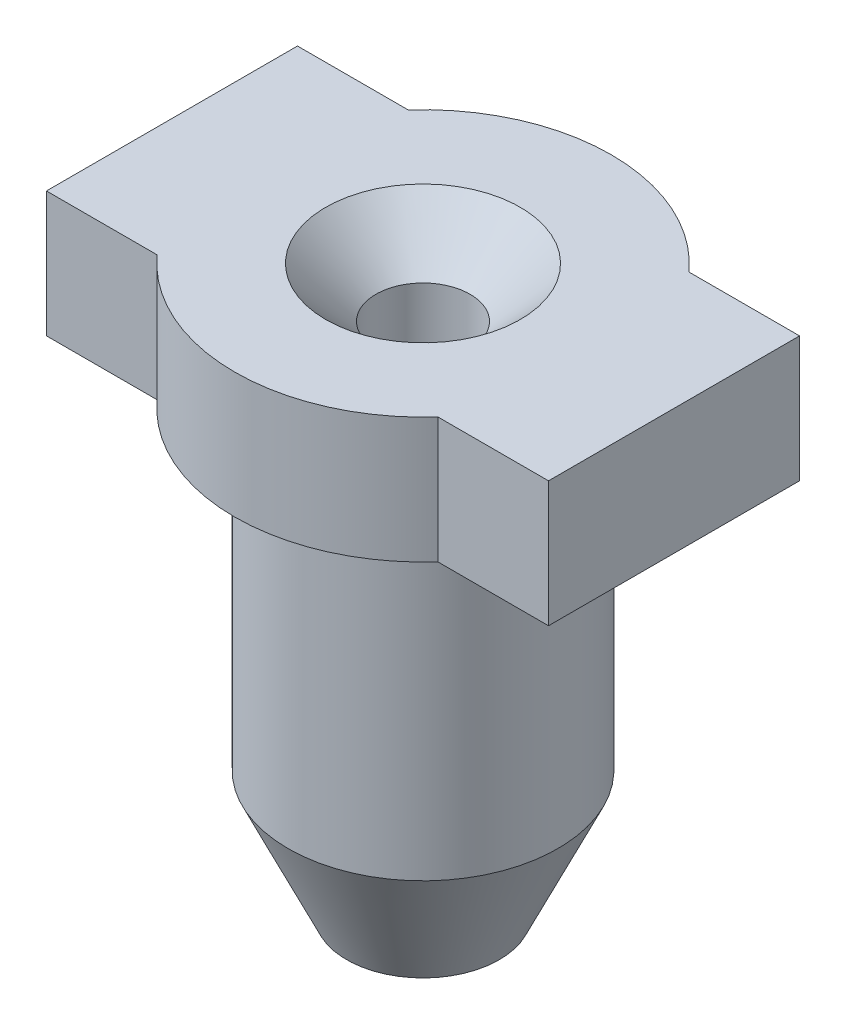
SolidWorks part; units mm, degrees
ref_plane "Front Plane" through (0, 0, 0) normal (0, 0, 1) x (1, 0, 0)
ref_plane "Top Plane" through (0, 0, 0) normal (0, 1, 0) x (1, 0, 0)
ref_plane "Right Plane" through (0, 0, 0) normal (1, 0, 0) x (0, 0, -1)
sketch "Sketch1" plane through (0, 0, 0) normal (0, 1, 0) x (1, 0, 0)
  circle A0 centre (0, 0) radius 15
  dimension "D1" = 30
extrude "Boss-Extrude1" add sketch "Sketch1" along normal blind 10
sketch "Sketch2" plane through (0, 0, 0) normal (0, -1, 0) x (1, 0, 0)
  circle A0 centre (0, 0) radius 10.75
  dimension "D1" = 21.5
extrude "Boss-Extrude2" add sketch "Sketch2" along normal blind 25
sketch "Sketch3" plane through (0, 10, 0) normal (0, 1, 0) x (1, 0, 0)
  circle A0 centre (0, 0) radius 3.75
  dimension "D1" = 7.5
extrude "Cut-Extrude1" cut sketch "Sketch3" against normal blind 28.8
sketch "Sketch5" plane through (0, -25, 0) normal (0, -1, 0) x (1, 0, 0)
  circle A1 centre (0, 0) radius 10.75
  circle A2 centre (0, 0) radius 10.75
  dimension "D1" = 0
extrude "Boss-Extrude4" add sketch "Sketch5" along normal blind 10 draft 25
chamfer "Chamfer1" distance 4 angle 45 1 edges at (0, 10, 3.75)
sketch "Sketch4" plane through (0, 10, 0) normal (0, 1, 0) x (1, 0, 0)
  line L1 (-20, 10) -> (20, 10)
  line L2 (-20, 10) -> (-20, -10)
  line L3 (-20, -10) -> (20, -10)
  line L4 (20, 10) -> (20, -10)
  line L5 (-20, 10) -> (20, -10) construction
  line L6 (-20, -10) -> (20, 10) construction
  point P0 (0, 0)
  dimension "D1" = 20
  dimension "D2" = 40
extrude "Boss-Extrude3" add sketch "Sketch4" against normal up to surface (10 mm away)
fillet "Fillet1" radius 3 1 edges at (0, 0, -10.75)
